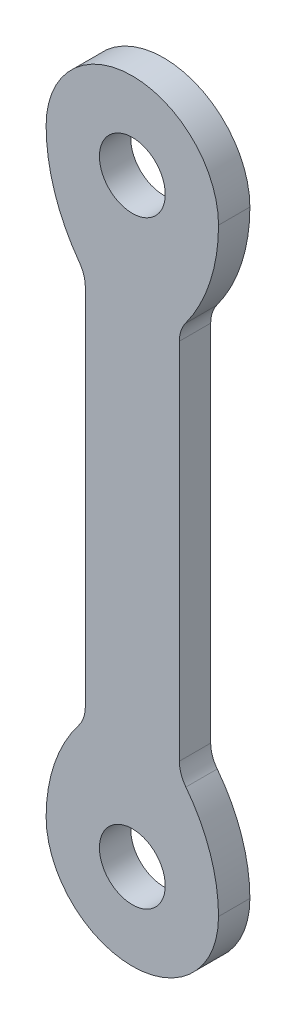
SolidWorks part; units mm, degrees
material "1.0553 (S355J0)"
ref_plane "Front Plane" through (0, 0, 0) normal (0, 0, 1) x (1, 0, 0)
ref_plane "Top Plane" through (0, 0, 0) normal (0, 1, 0) x (1, 0, 0)
ref_plane "Right Plane" through (0, 0, 0) normal (1, 0, 0) x (0, 0, -1)
sketch "Sketch1" plane through (0, 0, 0) normal (0, 0, 1) x (1, 0, 0)
  line L0 (-15, 152.6757) -> (-15, 36.6572)
  line L1 (15, 36.6572) -> (15, 152.6757)
  line L2 (0, 0) -> (0, 191) construction
  arc A1 (27.5, 191) -> (-27.5, 191) centre (0, 191) ccw
  arc A2 (-27.5, 0) -> (-17.0833, 30.5477) centre (22.5, 0) cw
  arc A3 (-27.5, 0) -> (27.5, 0) centre (0, 0) ccw
  arc A4 (27.5, 0) -> (17.0833, 30.5477) centre (-22.5, 0) ccw
  arc A5 (-17.0833, 30.5477) -> (-15, 36.6572) centre (-25, 36.6572) ccw
  arc A6 (17.0833, 30.5477) -> (15, 36.6572) centre (25, 36.6572) cw
  arc A7 (-27.5, 191) -> (-16.9231, 158.5718) centre (27.5, 191) ccw
  arc A8 (27.5, 191) -> (16.9231, 158.5718) centre (-27.5, 191) cw
  arc A9 (-16.9231, 158.5718) -> (-15, 152.6757) centre (-25, 152.6757) cw
  arc A10 (16.9231, 158.5718) -> (15, 152.6757) centre (25, 152.6757) ccw
  dimension "D1" = 27.5
  dimension "D2" = 27.5
  dimension "D5" = 50
  dimension "D6" = 10
  dimension "D8" = 10
  dimension "D3" = 191
  dimension "D4" = 30
extrude "Boss-Extrude1" add sketch "Sketch1" along normal blind 10
sketch "Sketch2" plane through (0, 0, 10) normal (0, 0, 1) x (1, 0, 0)
  circle A0 centre (0, 191) radius 10.5
  circle A1 centre (0, 0) radius 10.5
  dimension "D1" = 21
  dimension "D2" = 21
extrude "Cut-Extrude1" cut sketch "Sketch2" against normal up to next
sketch "Sketch3" [suppressed] plane through (0, 0, 10) normal (0, 0, 1) x (1, 0, 0)
  line L6 (0, 0) -> (0, -32.4998) construction
  line L7 (0, -27.5) -> (1.3397, -32.4998)
  line L8 (1.3397, -32.4998) -> (-0.7073, -32.4998)
  line L9 (-2.4386, -31.9498) -> (-15.8701, -22.4586)
  arc A0 (-27.5, 0) -> (27.5, 0) centre (0, 0) ccw construction
  arc A6 (-15.8701, -22.4586) -> (0, -27.5) centre (0, 0) ccw
  arc A7 (-0.7073, -32.4998) -> (-2.4386, -31.9498) centre (-0.7073, -29.4998) cw
  point P11 (-1.6603, -32.4998)
  dimension "D4" = 3
  dimension "D1" = 4.9998
  dimension "D2" = 3
  dimension "D3" = 15
extrude "Boss-Extrude2" [suppressed] add sketch "Sketch3" against normal up to surface (10 mm away)
sketch "Sketch4" [suppressed] plane through (0, 0, 10) normal (0, 0, 1) x (1, 0, 0)
  line L0 (40, 0) -> (0, 0) construction
  line L5 (17.0833, 30.5477) -> (46.9929, 10.361)
  line L6 (10.3125, -25.4932) -> (44.6875, -11.5878)
  arc A11 (44.6875, -11.5878) -> (46.9929, 10.361) centre (40, 0) ccw
  arc A12 (27.5, 0) -> (17.0833, 30.5477) centre (-22.5, 0) ccw construction
  arc A13 (27.5, 0) -> (17.0833, 30.5477) centre (-22.5, 0) ccw
  arc A14 (-27.5, 0) -> (27.5, 0) centre (0, 0) ccw construction
  arc A15 (10.3125, -25.4932) -> (27.5, 0) centre (0, 0) ccw
  dimension "D1" = 25
  dimension "D2" = 40
extrude "Boss-Extrude3" [suppressed] add sketch "Sketch4" against normal up to surface (10 mm away)
sketch "Sketch5" [suppressed] plane through (0, 0, 10) normal (0, 0, 1) x (1, 0, 0)
  circle A0 centre (40, 0) radius 8
  dimension "D1" = 16
extrude "Cut-Extrude2" [suppressed] cut sketch "Sketch5" against normal up to next
sketch "Sketch6" [suppressed] plane through (0, 0, 10) normal (0, 0, 1) x (1, 0, 0)
  line L0 (27.5, 0) -> (27.5, 143.4856)
  line L1 (27.5, 143.4856) -> (15, 143.4856)
  line L2 (15, 36.6572) -> (15, 152.6757) construction
  line L3 (15, 36.6572) -> (15, 143.4856)
  arc A0 (27.5, 0) -> (17.0833, 30.5477) centre (-22.5, 0) ccw construction
  arc A1 (27.5, 0) -> (17.0833, 30.5477) centre (-22.5, 0) ccw
  arc A2 (15, 36.6572) -> (17.0833, 30.5477) centre (25, 36.6572) ccw construction
  arc A3 (15, 36.6572) -> (17.0833, 30.5477) centre (25, 36.6572) ccw
extrude "Boss-Extrude4" [suppressed] add sketch "Sketch6" against normal up to surface (10 mm away)
